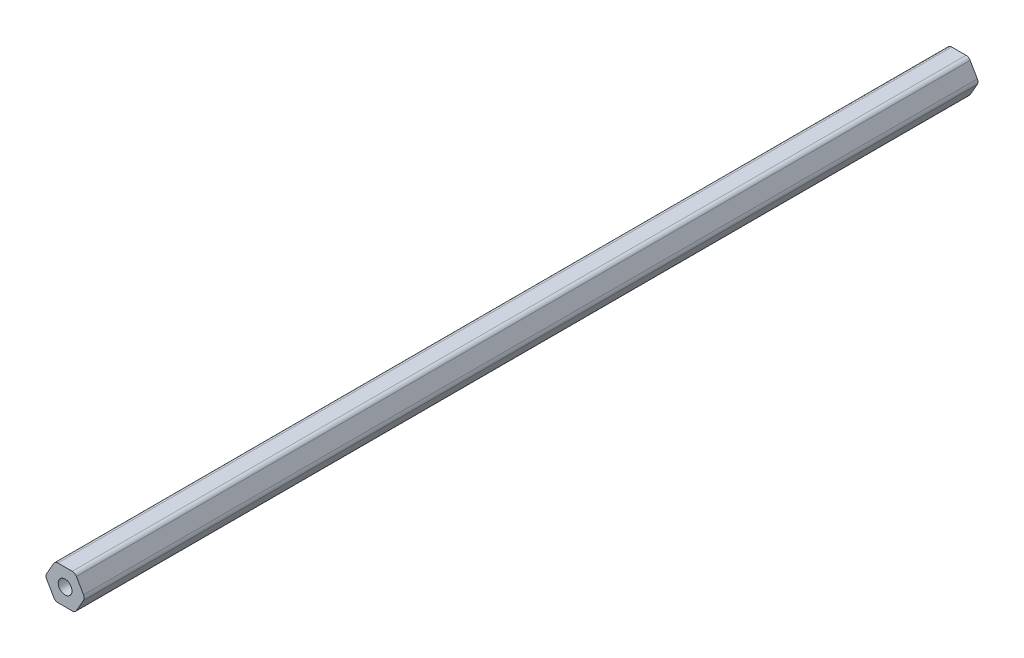
SolidWorks part; units mm, degrees
ref_plane "Front Plane" through (0, 0, 0) normal (0, 0, 1) x (1, 0, 0)
ref_plane "Top Plane" through (0, 0, 0) normal (0, 1, 0) x (1, 0, 0)
ref_plane "Right Plane" through (0, 0, 0) normal (1, 0, 0) x (0, 0, -1)
sketch "Sketch1" plane through (0, 0, 0) normal (0, 0, 1) x (1, 0, 0)
  line L1 (6.7083, 2.6911) -> (3.0421, 9.0411)
  line L2 (3.0421, 9.0411) -> (-4.2902, 9.0411)
  line L3 (-4.2902, 9.0411) -> (-7.9564, 2.6911)
  line L4 (-7.9564, 2.6911) -> (-4.2902, -3.6589)
  line L5 (-4.2902, -3.6589) -> (3.0421, -3.6589)
  line L6 (3.0421, -3.6589) -> (6.7083, 2.6911)
  circle A0 centre (-0.624, 2.6911) radius 6.35 construction
  circle A1 centre (-0.624, 2.6911) radius 2.54
  dimension "D1" = 12.7
extrude "Boss-Extrude1" add sketch "Sketch1" along normal blind 330.2
fillet "Fillet1" radius 1.778 6 edges at (-7.9564, 2.6911, 165.1) (-4.2902, 9.0411, 165.1) (-4.2902, -3.6589, 165.1) (3.0421, -3.6589, 165.1) (6.7083, 2.6911, 165.1) (3.0421, 9.0411, 165.1)
